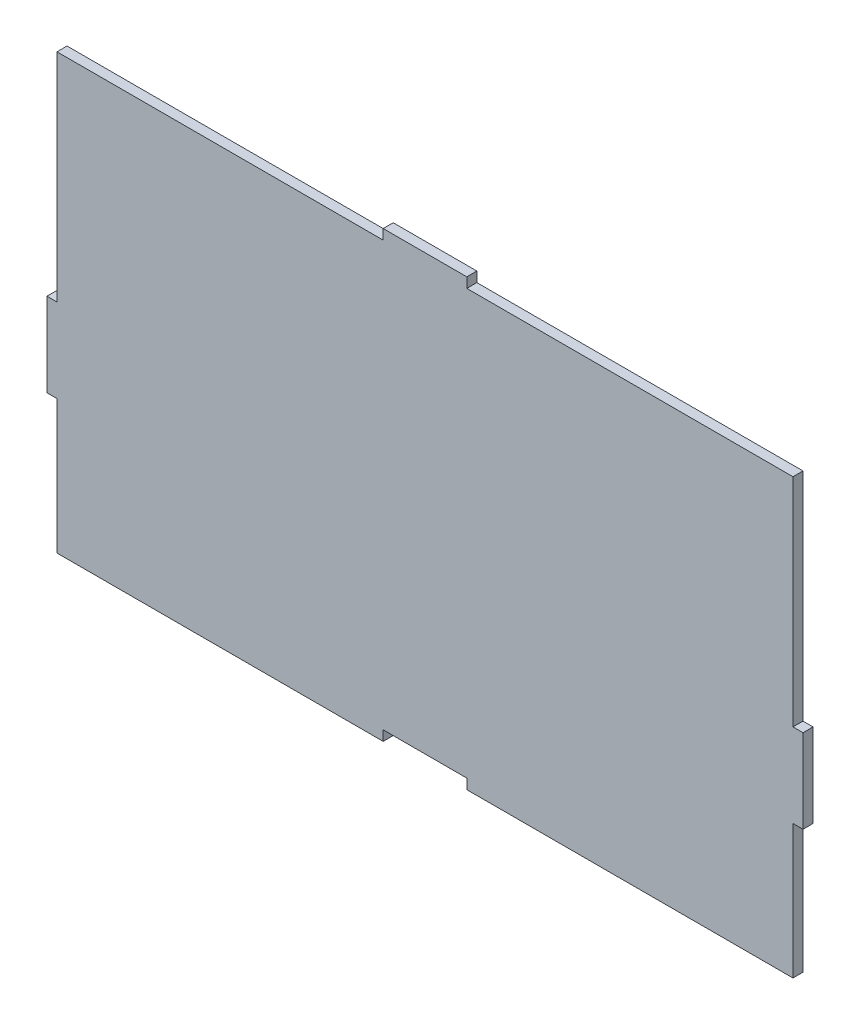
SolidWorks part; units mm, degrees
ref_plane "Спереди" through (0, 0, 0) normal (0, 0, 1) x (1, 0, 0)
ref_plane "Сверху" through (0, 0, 0) normal (0, 1, 0) x (1, 0, 0)
ref_plane "Справа" through (0, 0, 0) normal (1, 0, 0) x (0, 0, -1)
sketch "Эскиз1" plane through (0, 0, 0) normal (0, 0, 1) x (1, 0, 0)
  line L0 (-115.2137, -31.0428) -> (-115.2137, -71.0428)
  line L1 (-115.2137, 58.7272) -> (-17.7137, 58.7272)
  line L2 (-115.2137, 58.7272) -> (-115.2137, -6.0428)
  line L3 (-115.2137, -71.0428) -> (-17.7137, -71.0428)
  line L4 (104.7863, 58.7272) -> (104.7863, -6.0428)
  line L5 (-118.2137, -6.0428) -> (-115.2137, -6.0428)
  line L6 (-118.2137, -6.0428) -> (-118.2137, -31.0428)
  line L7 (-118.2137, -31.0428) -> (-115.2137, -31.0428)
  line L9 (104.7863, -6.0428) -> (107.7863, -6.0428)
  line L11 (104.7863, -31.0428) -> (107.7863, -31.0428)
  line L12 (107.7863, -6.0428) -> (107.7863, -31.0428)
  line L14 (-17.7137, 58.7272) -> (-17.7137, 61.7272)
  line L15 (-17.7137, 61.7272) -> (7.2863, 61.7272)
  line L16 (7.2863, 58.7272) -> (7.2863, 61.7272)
  line L18 (-17.7137, -71.0428) -> (-17.7137, -68.0428)
  line L19 (-17.7137, -68.0428) -> (7.2863, -68.0428)
  line L20 (7.2863, -71.0428) -> (7.2863, -68.0428)
  line L21 (7.2863, 58.7272) -> (104.7863, 58.7272)
  line L22 (7.2863, -71.0428) -> (104.7863, -71.0428)
  line L23 (104.7863, -31.0428) -> (104.7863, -71.0428)
  dimension "D1" = 25
  dimension "D2" = 25
  dimension "D3" = 25
  dimension "D4" = 25
  dimension "D5" = 3
  dimension "D6" = 3
  dimension "D7" = 3
  dimension "D8" = 3
  dimension "D9" = 220
  dimension "D10" = 129.77
  dimension "D11" = 40
  dimension "D12" = 40
  dimension "D13" = 97.5
  dimension "D14" = 97.5
extrude "Бобышка-Вытянуть1" add sketch "Эскиз1" along normal blind 3
